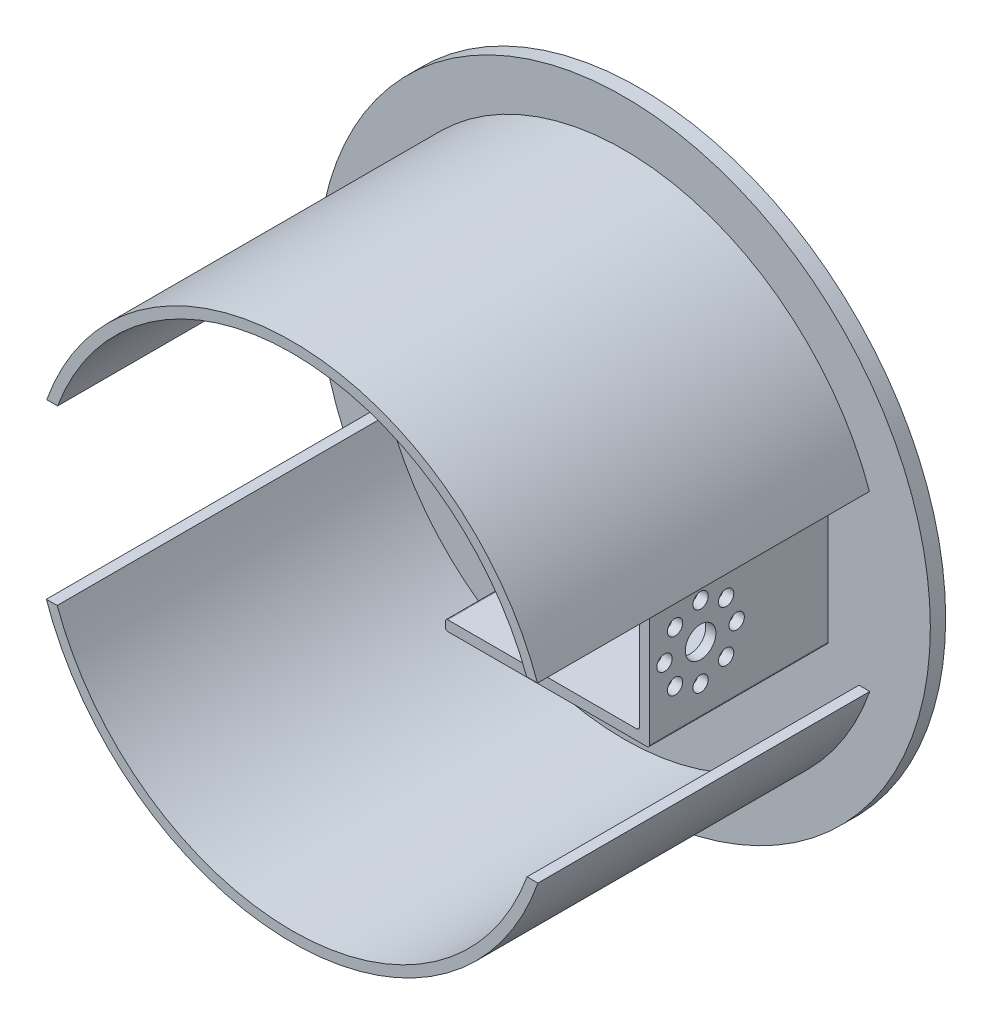
SolidWorks part; units mm, degrees
ref_plane "前视基准面" through (0, 0, 0) normal (0, 0, 1) x (1, 0, 0)
ref_plane "上视基准面" through (0, 0, 0) normal (0, 1, 0) x (1, 0, 0)
ref_plane "右视基准面" through (0, 0, 0) normal (1, 0, 0) x (0, 0, -1)
other "Configuration Table"
sketch "草图3" plane through (0, 0, 0) normal (0, 0, 1) x (1, 0, 0)
  circle A0 centre (0, 0) radius 48
  dimension "D1" = 96
extrude "凸台-拉伸2" add sketch "草图3" along normal blind 3
sketch "草图4" plane through (0, 0, 3) normal (0, 0, 1) x (1, 0, 0)
  circle A0 centre (0, 0) radius 3
  dimension "D1" = 6
extrude "切除-拉伸1" cut sketch "草图4" against normal blind 3
sketch "草图5" plane through (0, 0, 3) normal (0, 0, 1) x (1, 0, 0)
  line L0 (0, 0) -> (38, 0)
  line L1 (38, 0) -> (38, 10.5)
  line L2 (38, 0) -> (38, -10.5)
  line L3 (37.5, -11) -> (0.5, -11)
  line L4 (37.5, 11) -> (0.5, 11)
  line L5 (0, 11.5) -> (0, 12.5)
  line L6 (0.5, 13) -> (39.5, 13)
  line L7 (40, 12.5) -> (40, -12.5)
  line L8 (0, -11.5) -> (0, -12.5)
  line L9 (0.5, -13) -> (39.5, -13)
  arc A0 (0.5, -13) -> (0, -12.5) centre (0.5, -12.5) cw
  arc A1 (0, -11.5) -> (0.5, -11) centre (0.5, -11.5) cw
  arc A2 (39.5, -13) -> (40, -12.5) centre (39.5, -12.5) ccw
  arc A3 (37.5, -11) -> (38, -10.5) centre (37.5, -10.5) ccw
  arc A4 (40, 12.5) -> (39.5, 13) centre (39.5, 12.5) ccw
  arc A5 (38, 10.5) -> (37.5, 11) centre (37.5, 10.5) ccw
  arc A6 (0, 11.5) -> (0.5, 11) centre (0.5, 11.5) ccw
  arc A7 (0, 12.5) -> (0.5, 13) centre (0.5, 12.5) cw
  point P17 (40, -13)
  point P20 (38, -11)
  point P23 (40, 13)
  point P26 (38, 11)
  point P29 (0, 11)
  point P32 (0, 13)
  dimension "D7" = 0.5
  dimension "D1" = 38
  dimension "D2" = 11
  dimension "D3" = 11
  dimension "D4" = 2
  dimension "D5" = 40
  dimension "D6" = 26
extrude "凸台-拉伸3" add sketch "草图5" along normal blind 35 contours A7 L5 A6 L4 A5 L1 L2 A3 L3 A1 L8 A0 L9 A2 L7 A4 L6
sketch "草图6" plane through (40, 0, 0) normal (1, 0, 0) x (0, 0, -1)
  line L0 (-3, 0) -> (-25, 0)
  line L1 (-3, 48) -> (-3, -48) construction
  line L3 (-30, -5) -> (-20, -5)
  line L4 (-30, -5) -> (-30, 5)
  line L5 (-30, 5) -> (-20, 5)
  line L6 (-20, -5) -> (-20, 5)
  line L7 (-30, -5) -> (-20, 5) construction
  line L8 (-30, 5) -> (-20, -5) construction
  circle A0 centre (-25, 0) radius 3
  circle A1 centre (-30, 5) radius 1.5
  circle A2 centre (-20, 5) radius 1.5
  circle A3 centre (-20, -5) radius 1.5
  circle A4 centre (-30, -5) radius 1.5
  dimension "D2" = 6
  dimension "D5" = 3
  dimension "D1" = 22
  dimension "D3" = 10
  dimension "D4" = 10
  dimension "D6" = 4
extrude "切除-拉伸2" cut sketch "草图6" against normal blind 35
sketch "草图7" plane through (0, 0, 3) normal (0, 0, 1) x (1, 0, 0)
  line L0 (0, 0) -> (-35, 0)
  circle A4 centre (-35, 0) radius 1.55
  circle A5 centre (-24.7487, 24.7487) radius 1.55
  circle A6 centre (0, 35) radius 1.55
  circle A7 centre (24.7487, 24.7487) radius 1.55
  circle A8 centre (35, 0) radius 1.55
  circle A9 centre (24.7487, -24.7487) radius 1.55
  circle A10 centre (0, -35) radius 1.55
  circle A11 centre (-24.7487, -24.7487) radius 1.55
  dimension "D3" = 8
  dimension "D2" = 3.1
  dimension "D1" = 35
extrude "切除-拉伸5" cut sketch "草图7" against normal blind 35 contours A5 | A4 | A11 | A10 | A9 | A8 | A7 | A6
sketch "草图8" plane through (0, 0, 3) normal (0, 0, 1) x (1, 0, 0)
  circle A0 centre (0, 35) radius 2.05
  circle A1 centre (24.7487, 24.7487) radius 2.05
  circle A2 centre (35, 0) radius 2.05
  circle A3 centre (24.7487, -24.7487) radius 2.05
  circle A4 centre (0, -35) radius 2.05
  circle A5 centre (-24.7487, -24.7487) radius 2.05
  circle A6 centre (-35, 0) radius 2.05
  circle A7 centre (-24.7487, 24.7487) radius 2.05
  dimension "D1" = 4.1
  dimension "D2" = 8
extrude "切除-拉伸6" cut sketch "草图8" against normal blind 10
sketch "草图9" plane through (0, 0, 3) normal (0, 0, 1) x (1, 0, 0)
  line L1 (-5, -5) -> (5, -5)
  line L2 (-5, -5) -> (-5, 5)
  line L3 (-5, 5) -> (5, 5)
  line L4 (5, -5) -> (5, 5)
  line L5 (-5, -5) -> (5, 5) construction
  line L6 (-5, 5) -> (5, -5) construction
  circle A0 centre (-5, 5) radius 1.55
  circle A1 centre (5, 5) radius 1.55
  circle A2 centre (5, -5) radius 1.55
  circle A3 centre (-5, -5) radius 1.55
  point P0 (0, 0)
  dimension "D3" = 3.1
  dimension "D1" = 10
  dimension "D2" = 10
  dimension "D4" = 4
extrude "切除-拉伸7" cut sketch "草图9" against normal blind 10 contours A1 | A0 | A3 | A2
sketch "草图10" plane through (40, 0, 0) normal (1, 0, 0) x (0, 0, -1)
  line L1 (-38, 12.5) -> (-3, 12.5)
  line L2 (-38, 12.5) -> (-38, -12.5)
  line L3 (-38, -12.5) -> (-3, -12.5)
  line L4 (-3, 12.5) -> (-3, -12.5)
extrude "凸台-拉伸4" add sketch "草图10" against normal blind 2
sketch "草图11" plane through (40, 0, 0) normal (1, 0, 0) x (0, 0, -1)
  line L0 (-3, 0) -> (-28, 0)
  line L1 (-30, 5) -> (-20, 5) construction
  line L2 (-33, -5) -> (-23, -5)
  line L3 (-33, -5) -> (-33, 5)
  line L4 (-33, 5) -> (-23, 5)
  line L5 (-23, -5) -> (-23, 5)
  line L6 (-33, -5) -> (-23, 5) construction
  line L7 (-33, 5) -> (-23, -5) construction
  circle A0 centre (-28, 0) radius 3
  circle A1 centre (-33, 5) radius 1.5
  circle A2 centre (-28, 7.0711) radius 1.5
  circle A3 centre (-23, 5) radius 1.5
  circle A4 centre (-20.9289, 0) radius 1.5
  circle A5 centre (-23, -5) radius 1.5
  circle A6 centre (-28, -7.0711) radius 1.5
  circle A7 centre (-33, -5) radius 1.5
  circle A8 centre (-35.0711, 0) radius 1.5
  dimension "D2" = 6
  dimension "D4" = 3
  dimension "D1" = 25
  dimension "D3" = 10
  dimension "D5" = 8
extrude "切除-拉伸8" cut sketch "草图11" against normal blind 2 contours A1 | A8 | A7 | A6 | A5 | A4 | A3 | A2 | A0
sketch "草图12" plane through (0, 0, 3) normal (0, 0, 1) x (1, 0, 0)
  circle A0 centre (0, 0) radius 49
  circle A2 centre (0, 0) radius 48
  dimension "D1" = 98
extrude "凸台-拉伸5" add sketch "草图12" against normal blind 3
sketch "草图14" plane through (0, 0, 3) normal (0, 0, 1) x (1, 0, 0)
  circle A0 centre (0, 0) radius 49
  circle A1 centre (0, 0) radius 51
  dimension "D1" = 102
extrude "凸台-拉伸6" add sketch "草图14" along normal blind 65 separate body
sketch "草图15" plane through (0, 0, 0) normal (0, 0, -1) x (-1, 0, 0)
  circle A0 centre (0, 0) radius 49
  circle A1 centre (0, 0) radius 51
extrude "凸台-拉伸7" add sketch "草图15" against normal blind 3
sketch "草图16" plane through (0, 0, 0) normal (0, 0, -1) x (-1, 0, 0)
  circle A0 centre (0, 0) radius 51
  circle A1 centre (0, 0) radius 60
  dimension "D1" = 120
extrude "凸台-拉伸9" add sketch "草图16" against normal blind 3
sketch "草图19" plane through (40, 0, 0) normal (1, 0, 0) x (0, 0, -1)
  line L0 (-3, 51) -> (-3, -51) construction
  line L1 (-3, 17.0546) -> (-68, 17.0546)
  line L2 (-3, 17.0546) -> (-3, -16.8287)
  line L3 (-3, -16.8287) -> (-68, -16.8287)
  line L4 (-68, 17.0546) -> (-68, -16.8287)
  line L5 (-68, 51) -> (-68, -51) construction
extrude "切除-拉伸9" cut sketch "草图19" along normal through all
sketch "草图20" plane through (38, 0, 0) normal (-1, 0, 0) x (0, 0, 1)
  line L1 (68, 17.0546) -> (3, 17.0546)
  line L2 (68, 17.0546) -> (68, -16.8287)
  line L3 (68, -16.8287) -> (3, -16.8287)
  line L4 (3, 17.0546) -> (3, -16.8287)
ref_plane "基准面1" through (-2, 0, 0) normal (-1, 0, 0) x (0, 0, 1)
sketch "草图21" plane through (-2, 0, 0) normal (-1, 0, 0) x (0, 0, 1)
  line L1 (3, 17.0546) -> (68, 17.0546)
  line L2 (3, 17.0546) -> (3, -16.8287)
  line L3 (3, -16.8287) -> (68, -16.8287)
  line L4 (68, 17.0546) -> (68, -16.8287)
extrude "切除-拉伸10" cut sketch "草图21" along normal through all
